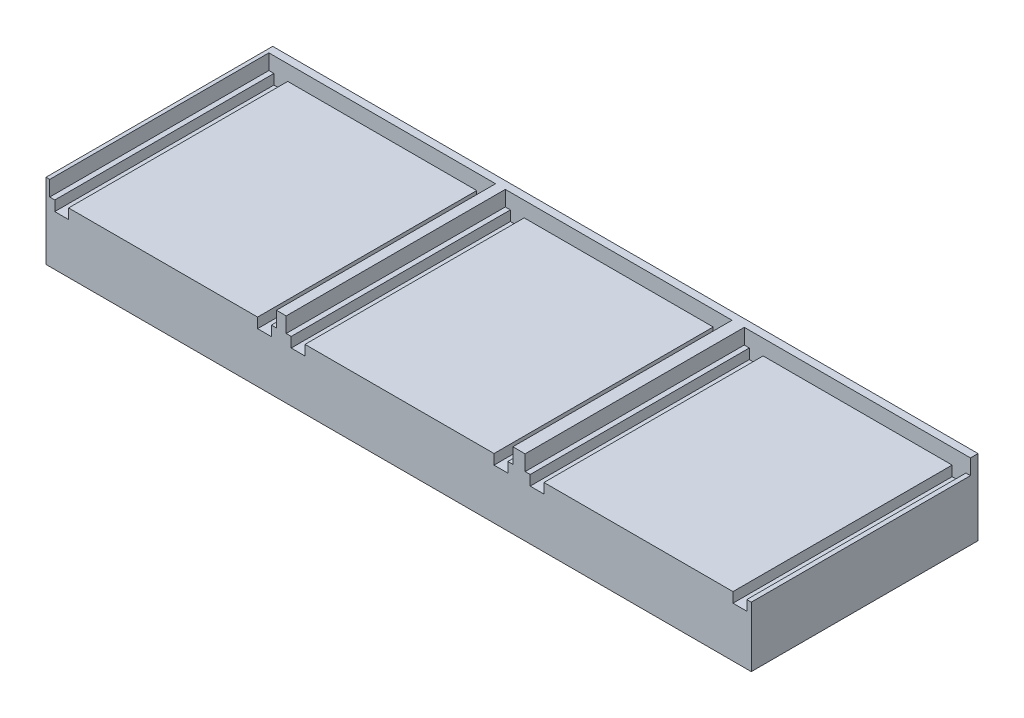
SolidWorks part; units mm, degrees
ref_plane "Front Plane" through (0, 0, 0) normal (0, 0, 1) x (1, 0, 0)
ref_plane "Top Plane" through (0, 0, 0) normal (0, 1, 0) x (1, 0, 0)
ref_plane "Right Plane" through (0, 0, 0) normal (1, 0, 0) x (0, 0, -1)
sketch "Sketch1" plane through (0, 0, 0) normal (0, 1, 0) x (1, 0, 0)
  line L5 (250, -90) -> (110, -90)
  line L6 (110, -90) -> (110, 0)
  line L7 (250, -90) -> (390, -90)
  line L8 (390, -90) -> (390, 0)
  line L9 (390, 0) -> (110, 0)
extrude "Boss-Extrude1" add sketch "Sketch1" along normal blind 30
sketch "Sketch3" plane through (0, 0, 90) normal (0, 0, 1) x (1, 0, 0)
  line L0 (113.4831, 23.9205) -> (111.4831, 23.9205)
  line L1 (302.2101, 23.9005) -> (300.2101, 23.9005)
  line L2 (207.3484, 23.9421) -> (205.3484, 23.9421)
  line L3 (207.3484, 23.9421) -> (207.3484, 19.9421)
  line L4 (207.3484, 19.9421) -> (212.8318, 19.9421)
  line L5 (212.8318, 19.9421) -> (212.8318, 23.9421)
  line L6 (212.8318, 23.9421) -> (287.8649, 23.9421)
  line L7 (205.3484, 23.9421) -> (205.3484, 30.003)
  line L8 (205.3484, 30.003) -> (295.3484, 30.003)
  line L9 (250.3484, 30.003) -> (250.3484, 23.9421)
  line L10 (250.3484, 23.9421) -> (253.3093, 23.9421)
  line L11 (295.3484, 23.9421) -> (295.3484, 30.003)
  line L12 (293.3484, 23.9421) -> (295.3484, 23.9421)
  line L13 (293.3484, 23.9421) -> (293.3484, 19.9421)
  line L14 (293.3484, 19.9421) -> (287.8649, 19.9421)
  line L15 (287.8649, 19.9421) -> (287.8649, 23.9421)
  line L16 (113.4831, 23.9205) -> (113.4831, 19.9205)
  line L17 (113.4831, 19.9205) -> (118.9665, 19.9205)
  line L18 (118.9665, 19.9205) -> (118.9665, 23.9205)
  line L19 (118.9665, 23.9205) -> (193.9996, 23.9205)
  line L20 (111.4831, 23.9205) -> (111.4831, 30.1151)
  line L21 (111.4831, 30.1151) -> (201.4831, 30.1151)
  line L22 (156.4831, 30.1151) -> (156.4831, 23.9205)
  line L23 (156.4831, 23.9205) -> (159.444, 23.9205)
  line L24 (201.4831, 23.9205) -> (201.4831, 30.1151)
  line L25 (199.4831, 23.9205) -> (201.4831, 23.9205)
  line L26 (199.4831, 23.9205) -> (199.4831, 19.9205)
  line L27 (199.4831, 19.9205) -> (193.9996, 19.9205)
  line L28 (193.9996, 19.9205) -> (193.9996, 23.9205)
  line L30 (302.2101, 23.9005) -> (302.2101, 19.9005)
  line L31 (302.2101, 19.9005) -> (307.6935, 19.9005)
  line L32 (307.6935, 19.9005) -> (307.6935, 23.9005)
  line L33 (307.6935, 23.9005) -> (382.7267, 23.9005)
  line L34 (300.2101, 23.9005) -> (300.2101, 30.4594)
  line L35 (300.2101, 30.4594) -> (390.2101, 30.4594)
  line L36 (345.2101, 30.4594) -> (345.2101, 23.9005)
  line L37 (345.2101, 23.9005) -> (348.1711, 23.9005)
  line L38 (390.2101, 23.9005) -> (390.2101, 30.4594)
  line L39 (388.2101, 23.9005) -> (390.2101, 23.9005)
  line L40 (388.2101, 23.9005) -> (388.2101, 19.9005)
  line L41 (388.2101, 19.9005) -> (382.7267, 19.9005)
  line L42 (382.7267, 19.9005) -> (382.7267, 23.9005)
extrude "Cut-Extrude1" cut sketch "Sketch3" against normal blind 87 contours L2 L7 L8 L11 L12 L13 L14 L15 L6 L5 L4 L3 | L19 L28 L27 L26 L25 L24 L21 L20 L0 L16 L17 L18 | L35 L38 L39 L40 L41 L42 L33 L32 L31 L30 L1 L34
